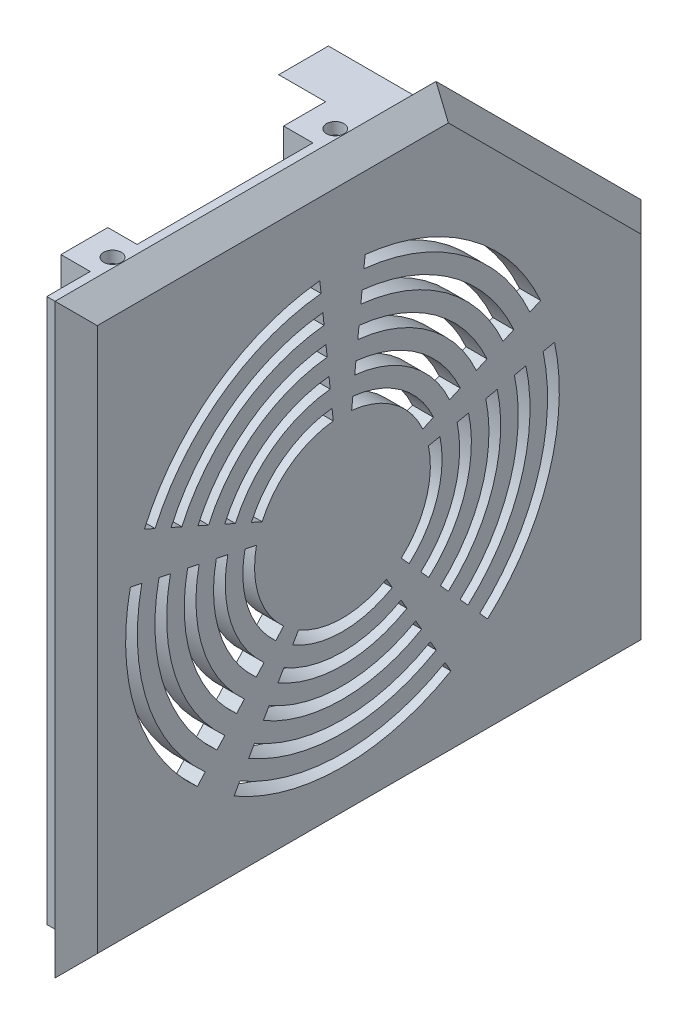
SolidWorks part; units mm, degrees
ref_plane "Front Plane" through (0, 0, 0) normal (0, 0, 1) x (1, 0, 0)
ref_plane "Top Plane" through (0, 0, 0) normal (0, 1, 0) x (1, 0, 0)
ref_plane "Right Plane" through (0, 0, 0) normal (1, 0, 0) x (0, 0, -1)
sketch "Sketch1" plane through (0, 0, 0) normal (1, 0, 0) x (0, 0, -1)
  line L0 (-8.4475, 4.8927) -> (-8.4475, -95.1073)
  line L1 (-8.4475, -95.1073) -> (91.5525, -95.1073)
  line L2 (91.5525, -95.1073) -> (91.5525, -30.1073)
  line L3 (91.5525, -30.1073) -> (56.5525, 4.8927)
  line L4 (56.5525, 4.8927) -> (-8.4475, 4.8927)
  dimension "D1" = 100
  dimension "D2" = 100
  dimension "D3" = 135
  dimension "D4" = 65
extrude "Boss-Extrude1" add sketch "Sketch1" along normal blind 3.6 draft 45
sketch "Sketch2" plane through (0, 0, 0) normal (-1, 0, 0) x (0, 0, 1)
  line L0 (-56.1927, 1.2927) -> (4.8475, 1.2927) construction
  line L1 (4.8475, 1.2927) -> (4.8475, -91.5073) construction
  line L2 (4.8475, -91.5073) -> (-87.9525, -91.5073) construction
  line L3 (-87.9525, -91.5073) -> (-87.9525, -30.4671) construction
  line L4 (-87.9525, -30.4671) -> (-56.1927, 1.2927) construction
  line L5 (-56.5525, 4.8927) -> (8.4475, 4.8927) construction
  line L6 (8.4475, 4.8927) -> (8.4475, -95.1073) construction
  line L7 (-91.5525, -95.1073) -> (-91.5525, -30.1073) construction
  line L8 (8.4475, -95.1073) -> (-91.5525, -95.1073) construction
  line L9 (-91.5525, -30.1073) -> (-56.5525, 4.8927) construction
  line L10 (-56.1927, 1.2927) -> (4.8475, 1.2927)
  line L11 (4.8475, 1.2927) -> (4.8475, -91.5073)
  line L12 (4.8475, -91.5073) -> (-87.9525, -91.5073)
  line L13 (-87.9525, -91.5073) -> (-87.9525, -30.4671)
  line L14 (-87.9525, -30.4671) -> (-56.1927, 1.2927)
  dimension "D1" = 3.6
  dimension "D2" = 3.6
  dimension "D3" = 3.6
  dimension "D4" = 3.6
  dimension "D5" = 3.6
  dimension "D6" = 2.8
extrude "Extrude-Thin2" add sketch "Sketch2" along normal blind 5 thin
sketch "Sketch5" plane through (0, 0, 0) normal (-1, 0, 0) x (0, 0, 1)
  line L0 (4.8475, -91.5073) -> (-87.9525, -91.5073) construction
  line L1 (-70.5525, -91.5073) -> (-62.5525, -91.5073)
  line L2 (-70.5525, -91.5073) -> (-70.5525, -83.5073)
  line L3 (-70.5525, -83.5073) -> (-62.5525, -83.5073)
  line L4 (-62.5525, -91.5073) -> (-62.5525, -83.5073)
  line L5 (-91.5525, -95.1073) -> (-91.5525, -30.1073) construction
  line L6 (-20.5525, -91.5073) -> (-12.5525, -91.5073)
  line L7 (-20.5525, -91.5073) -> (-20.5525, -83.5073)
  line L8 (-20.5525, -83.5073) -> (-12.5525, -83.5073)
  line L9 (-12.5525, -91.5073) -> (-12.5525, -83.5073)
  line L10 (8.4475, 4.8927) -> (8.4475, -95.1073) construction
  point P10 (-66.5525, -83.5073)
  point P13 (-16.5525, -83.5073)
  dimension "D1" = 8
  dimension "D2" = 25
  dimension "8" = 8
  dimension "D3" = 25
extrude "Boss-Extrude2" add sketch "Sketch5" along normal blind 10
ref_plane "Plane1" through (0, -85.5073, 0) normal (0, 1, 0) x (1, 0, 0)
sketch "Sketch6" plane through (0, -85.5073, 0) normal (0, 1, 0) x (1, 0, 0)
  line L5 (-10, 69.5525) -> (-3.7321, 69.5525)
  line L6 (-10, 70.5525) -> (-10, 62.5525) construction
  line L7 (-3.7321, 69.5525) -> (-2, 66.5525)
  line L8 (-2, 66.5525) -> (-3.7321, 63.5525)
  line L9 (-3.7321, 63.5525) -> (-10, 63.5525)
  line L10 (-10, 63.5525) -> (-10, 69.5525)
  line L16 (-10, 19.5525) -> (-3.7321, 19.5525)
  line L17 (-3.7321, 19.5525) -> (-2, 16.5525)
  line L18 (-2, 16.5525) -> (-3.7321, 13.5525)
  line L19 (-3.7321, 13.5525) -> (-10, 13.5525)
  line L20 (-10, 13.5525) -> (-10, 19.5525)
  line L21 (-10, 20.5525) -> (-10, 12.5525) construction
  point P12 (-10, 66.5525)
  point P13 (-10, 66.5525)
  point P21 (-10, 16.5525)
  point P22 (-10, 16.5525)
  dimension "D1" = 6
  dimension "D2" = 8
  dimension "D6" = 120
  dimension "D7" = 6
  dimension "D8" = 120
  dimension "D9" = 8
extrude "Cut-Extrude1" cut sketch "Sketch6" against normal blind 4
hole_wizard "Ø3.0mm Dowel Hole1" positions "Sketch9" profile "Sketch10" hole size "Ø3.0" standard "BSI"
sketch "Sketch9" plane through (0, -91.5073, 0) normal (0, -1, 0) x (-1, 0, 0)
  point P0 (5.2, 66.5525)
  point P2 (5.2, 16.5525)
  dimension "D1" = 3.2
sketch "Sketch10" plane through (-5.2, -91.5073, -66.5525) normal (1, 0, 0) x (0, 0, -1)
  line L0 (0, 0) -> (0, 8.9013)
  line L1 (0, 8.9013) -> (1.5, 8)
  line L2 (1.5, 8) -> (1.5, 0)
  line L5 (1.5, 0) -> (0, 0)
  line L10 (0, 8.9013) -> (-1.5, 8) construction
  line L11 (0, -6.35) -> (0, 107.95) construction
  dimension "Hole Dia." = 3
  dimension "Hole Depth" = 8
  dimension "Drill Angle" = 118
sketch "Sketch11" plane through (0, 0, 0) normal (-1, 0, 0) x (0, 0, 1)
  line L0 (-56.1927, 1.2927) -> (4.8475, 1.2927) construction
  line L1 (-2.5525, 1.2927) -> (-10.5525, 1.2927)
  line L2 (-2.5525, 1.2927) -> (-2.5525, -6.7073)
  line L3 (-2.5525, -6.7073) -> (-10.5525, -6.7073)
  line L4 (-10.5525, 1.2927) -> (-10.5525, -6.7073)
  line L5 (-62.5525, -83.5073) -> (-70.5525, -83.5073) construction
  line L6 (-48.5525, 1.2927) -> (-40.5525, 1.2927)
  line L7 (-48.5525, 1.2927) -> (-48.5525, -6.7073)
  line L8 (-48.5525, -6.7073) -> (-40.5525, -6.7073)
  line L9 (-40.5525, 1.2927) -> (-40.5525, -6.7073)
  line L10 (-62.5525, -91.5073) -> (-62.5525, -83.5073) construction
  line L13 (8.4475, 4.8927) -> (8.4475, -95.1073) construction
  point P16 (-44.5525, 1.2927)
  point P19 (-6.5525, 1.2927)
  dimension "D1" = 15
  dimension "D2" = 12
extrude "Boss-Extrude3" add sketch "Sketch11" along normal up to surface (10 mm away)
ref_plane "Plane2" through (0, -0.7073, 0) normal (0, 1, 0) x (1, 0, 0)
sketch "Sketch13" plane through (0, -0.7073, 0) normal (0, 1, 0) x (1, 0, 0)
  line L0 (-10, 9.5525) -> (-3.7321, 9.5525)
  line L1 (-3.7321, 9.5525) -> (-2, 6.5525)
  line L2 (-2, 6.5525) -> (-3.7321, 3.5525)
  line L3 (-3.7321, 3.5525) -> (-10, 3.5525)
  line L4 (-10, 3.5525) -> (-10, 9.5525)
  line L5 (-10, 10.5525) -> (-10, 2.5525) construction
  line L6 (-10, 47.5525) -> (-3.7321, 47.5525)
  line L7 (-3.7321, 47.5525) -> (-2, 44.5525)
  line L8 (-2, 44.5525) -> (-3.7321, 41.5525)
  line L9 (-3.7321, 41.5525) -> (-10, 41.5525)
  line L10 (-10, 41.5525) -> (-10, 47.5525)
  line L11 (-10, 48.5525) -> (-10, 40.5525) construction
  point P7 (-10, 6.5525)
  point P8 (-10, 6.5525)
  point P14 (-10, 44.5525)
  point P17 (-10, 44.5525)
  dimension "D1" = 6
  dimension "D2" = 120
  dimension "D3" = 8
  dimension "D4" = 6
  dimension "D5" = 120
  dimension "D6" = 8
extrude "Cut-Extrude2" cut sketch "Sketch13" against normal blind 4
hole_wizard "Ø3.0mm Dowel Hole2" positions "Sketch14" profile "Sketch15" hole size "Ø3.0" standard "BSI"
sketch "Sketch14" plane through (0, 1.2927, 0) normal (0, 1, 0) x (1, 0, 0)
  point P0 (-122.1853, 54.0527)
  point P2 (-5.2, 44.5525)
  point P4 (-5.2, 6.5525)
  dimension "D1" = 3.2
  dimension "D2" = 3.2
sketch "Sketch15" plane through (-122.1853, 1.2927, -54.0527) normal (1, 0, 0) x (0, 0, 1)
  line L0 (0, 0) -> (0, 8.9013)
  line L1 (0, 8.9013) -> (1.5, 8)
  line L2 (1.5, 8) -> (1.5, 0)
  line L5 (1.5, 0) -> (0, 0)
  line L10 (0, 8.9013) -> (-1.5, 8) construction
  line L11 (0, -6.35) -> (0, 107.95) construction
  dimension "Hole Dia." = 3
  dimension "Hole Depth" = 8
  dimension "Drill Angle" = 118
sketch "Sketch16" plane through (0, 0, 0) normal (-1, 0, 0) x (0, 0, 1)
  line L0 (-56.1927, 1.2927) -> (4.8475, 1.2927) construction
  line L1 (-47.7074, 1.2927) -> (-87.9525, -38.9524)
  line L2 (-87.9525, -91.5073) -> (-87.9525, -30.4671) construction
  line L3 (-87.9525, -38.9524) -> (-87.9525, -30.4671)
  line L4 (-87.9525, -30.4671) -> (-56.1927, 1.2927)
  line L5 (-56.1927, 1.2927) -> (-47.7074, 1.2927)
  dimension "D1" = 6
extrude "Boss-Extrude4" add sketch "Sketch16" along normal blind 18
sketch "Sketch17" plane through (-18, 0, 0) normal (-1, 0, 0) x (0, 0, 1)
  line L0 (-57.2234, -2.8492) -> (-55.8092, -4.2634)
  line L1 (-55.8092, -4.2634) -> (-82.3964, -30.8507)
  line L2 (-82.3964, -30.8507) -> (-83.8106, -29.4364)
  line L3 (-83.8106, -29.4364) -> (-57.2234, -2.8492)
  line L4 (-91.5525, -30.1073) -> (-56.5525, 4.8927) construction
  line L5 (-87.9525, -30.4671) -> (-56.1927, 1.2927) construction
  line L6 (-74.0525, -12.6073) -> (-70.517, -16.1428) construction
  dimension "D1" = 2
  dimension "D2" = 2.2
  dimension "D3" = 37.6
extrude "Cut-Extrude3" cut sketch "Sketch17" against normal blind 6
sketch "Sketch18" plane through (0, 0, 0) normal (-1, 0, 0) x (0, 0, 1)
  line L24 (-36.9898, -47.8542) -> (-12.6985, -89.928) construction
  line L25 (-36.9898, -47.8542) -> (-61.2476, -89.8699) construction
  line L26 (-29.4898, -60.8446) -> (-28.4898, -62.5766)
  line L27 (-26.9898, -65.1747) -> (-25.9898, -66.9068)
  line L28 (-24.4898, -69.5048) -> (-23.4898, -71.2369)
  line L29 (-21.9898, -73.835) -> (-20.9898, -75.567)
  line L30 (-44.4898, -60.8446) -> (-45.4898, -62.5766)
  line L31 (-46.9898, -65.1747) -> (-47.9898, -66.9068)
  line L32 (-49.4898, -69.5048) -> (-50.4898, -71.2369)
  line L33 (-51.9898, -73.835) -> (-52.9898, -75.567)
  line L34 (-19.4898, -78.1651) -> (-18.4898, -79.8971)
  line L35 (-54.4898, -78.1651) -> (-55.4898, -79.8971)
  line L36 (-47.0268, -59.0014) -> (-48.365, -60.4877)
  line L37 (-50.3724, -62.7171) -> (-51.7107, -64.2034)
  line L38 (-53.7181, -66.4328) -> (-55.0564, -67.9191)
  line L39 (-57.0637, -70.1485) -> (-58.402, -71.6348)
  line L40 (-51.662, -44.7355) -> (-53.6183, -44.3197)
  line L41 (-56.5528, -43.696) -> (-58.5091, -43.2801)
  line L42 (-61.4435, -42.6564) -> (-63.3998, -42.2406)
  line L43 (-66.3343, -41.6168) -> (-68.2905, -41.201)
  line L44 (-60.4094, -73.8643) -> (-61.7477, -75.3506)
  line L45 (-71.225, -40.5773) -> (-73.1813, -40.1615)
  line L46 (-50.693, -41.7531) -> (-52.5201, -40.9397)
  line L47 (-55.2607, -39.7195) -> (-57.0878, -38.906)
  line L48 (-59.8285, -37.6858) -> (-61.6556, -36.8723)
  line L49 (-64.3962, -35.6521) -> (-66.2233, -34.8386)
  line L50 (-38.5578, -32.9364) -> (-38.7668, -30.9473)
  line L51 (-39.0804, -27.9638) -> (-39.2895, -25.9747)
  line L52 (-39.603, -22.9911) -> (-39.8121, -21.0021)
  line L53 (-40.1257, -18.0185) -> (-40.3347, -16.0295)
  line L54 (-68.9639, -33.6184) -> (-70.791, -32.8049)
  line L55 (-40.6483, -13.0459) -> (-40.8574, -11.0569)
  line L56 (-35.4219, -32.9364) -> (-35.2128, -30.9473)
  line L57 (-34.8993, -27.9638) -> (-34.6902, -25.9747)
  line L58 (-34.3766, -22.9911) -> (-34.1676, -21.0021)
  line L59 (-33.854, -18.0185) -> (-33.6449, -16.0295)
  line L60 (-23.2866, -41.7531) -> (-21.4596, -40.9397)
  line L61 (-18.7189, -39.7195) -> (-16.8918, -38.906)
  line L62 (-14.1512, -37.6858) -> (-12.3241, -36.8723)
  line L63 (-9.5835, -35.6521) -> (-7.7564, -34.8386)
  line L64 (-33.3313, -13.0459) -> (-33.1223, -11.0569)
  line L65 (-5.0157, -33.6184) -> (-3.1886, -32.8049)
  line L66 (-22.3176, -44.7355) -> (-20.3613, -44.3197)
  line L67 (-17.4269, -43.696) -> (-15.4706, -43.2801)
  line L68 (-12.5361, -42.6564) -> (-10.5798, -42.2406)
  line L69 (-7.6454, -41.6168) -> (-5.6891, -41.201)
  line L70 (-26.9529, -59.0014) -> (-25.6146, -60.4877)
  line L71 (-23.6072, -62.7171) -> (-22.269, -64.2034)
  line L72 (-20.2616, -66.4328) -> (-18.9233, -67.9191)
  line L73 (-16.9159, -70.1485) -> (-15.5776, -71.6348)
  line L74 (-2.7547, -40.5773) -> (-0.7984, -40.1615)
  line L75 (-13.5703, -73.8643) -> (-12.232, -75.3506)
  arc A0 (-29.4898, -60.8446) -> (-44.4898, -60.8446) centre (-36.9898, -47.8542) cw
  arc A1 (-28.4898, -62.5766) -> (-45.4898, -62.5766) centre (-36.9898, -47.8542) cw
  arc A2 (-26.9898, -65.1747) -> (-46.9898, -65.1747) centre (-36.9898, -47.8542) cw
  arc A3 (-25.9898, -66.9068) -> (-47.9898, -66.9068) centre (-36.9898, -47.8542) cw
  arc A4 (-24.4898, -69.5048) -> (-49.4898, -69.5048) centre (-36.9898, -47.8542) cw
  arc A5 (-23.4898, -71.2369) -> (-50.4898, -71.2369) centre (-36.9898, -47.8542) cw
  arc A6 (-21.9898, -73.835) -> (-51.9898, -73.835) centre (-36.9898, -47.8542) cw
  arc A7 (-20.9898, -75.567) -> (-52.9898, -75.567) centre (-36.9898, -47.8542) cw
  arc A8 (-19.4898, -78.1651) -> (-54.4898, -78.1651) centre (-36.9898, -47.8542) cw
  arc A9 (-18.4898, -79.8971) -> (-55.4898, -79.8971) centre (-36.9898, -47.8542) cw
  arc A10 (-47.0268, -59.0014) -> (-51.662, -44.7355) centre (-36.9898, -47.8542) cw
  arc A11 (-48.365, -60.4877) -> (-53.6183, -44.3197) centre (-36.9898, -47.8542) cw
  arc A12 (-50.3724, -62.7171) -> (-56.5528, -43.696) centre (-36.9898, -47.8542) cw
  arc A13 (-51.7107, -64.2034) -> (-58.5091, -43.2801) centre (-36.9898, -47.8542) cw
  arc A14 (-53.7181, -66.4328) -> (-61.4435, -42.6564) centre (-36.9898, -47.8542) cw
  arc A15 (-55.0564, -67.9191) -> (-63.3998, -42.2406) centre (-36.9898, -47.8542) cw
  arc A16 (-57.0637, -70.1485) -> (-66.3343, -41.6168) centre (-36.9898, -47.8542) cw
  arc A17 (-58.402, -71.6348) -> (-68.2905, -41.201) centre (-36.9898, -47.8542) cw
  arc A18 (-60.4094, -73.8643) -> (-71.225, -40.5773) centre (-36.9898, -47.8542) cw
  arc A19 (-61.7477, -75.3506) -> (-73.1813, -40.1615) centre (-36.9898, -47.8542) cw
  arc A20 (-50.693, -41.7531) -> (-38.5578, -32.9364) centre (-36.9898, -47.8542) cw
  arc A21 (-52.5201, -40.9397) -> (-38.7668, -30.9473) centre (-36.9898, -47.8542) cw
  arc A22 (-55.2607, -39.7195) -> (-39.0804, -27.9638) centre (-36.9898, -47.8542) cw
  arc A23 (-57.0878, -38.906) -> (-39.2895, -25.9747) centre (-36.9898, -47.8542) cw
  arc A24 (-59.8285, -37.6858) -> (-39.603, -22.9911) centre (-36.9898, -47.8542) cw
  arc A25 (-61.6556, -36.8723) -> (-39.8121, -21.0021) centre (-36.9898, -47.8542) cw
  arc A26 (-64.3962, -35.6521) -> (-40.1257, -18.0185) centre (-36.9898, -47.8542) cw
  arc A27 (-66.2233, -34.8386) -> (-40.3347, -16.0295) centre (-36.9898, -47.8542) cw
  arc A28 (-68.9639, -33.6184) -> (-40.6483, -13.0459) centre (-36.9898, -47.8542) cw
  arc A29 (-70.791, -32.8049) -> (-40.8574, -11.0569) centre (-36.9898, -47.8542) cw
  arc A30 (-35.4219, -32.9364) -> (-23.2866, -41.7531) centre (-36.9898, -47.8542) cw
  arc A31 (-35.2128, -30.9473) -> (-21.4596, -40.9397) centre (-36.9898, -47.8542) cw
  arc A32 (-34.8993, -27.9638) -> (-18.7189, -39.7195) centre (-36.9898, -47.8542) cw
  arc A33 (-34.6902, -25.9747) -> (-16.8918, -38.906) centre (-36.9898, -47.8542) cw
  arc A34 (-34.3766, -22.9911) -> (-14.1512, -37.6858) centre (-36.9898, -47.8542) cw
  arc A35 (-34.1676, -21.0021) -> (-12.3241, -36.8723) centre (-36.9898, -47.8542) cw
  arc A36 (-33.854, -18.0185) -> (-9.5835, -35.6521) centre (-36.9898, -47.8542) cw
  arc A37 (-33.6449, -16.0295) -> (-7.7564, -34.8386) centre (-36.9898, -47.8542) cw
  arc A38 (-33.3313, -13.0459) -> (-5.0157, -33.6184) centre (-36.9898, -47.8542) cw
  arc A39 (-33.1223, -11.0569) -> (-3.1886, -32.8049) centre (-36.9898, -47.8542) cw
  arc A40 (-22.3176, -44.7355) -> (-26.9529, -59.0014) centre (-36.9898, -47.8542) cw
  arc A41 (-20.3613, -44.3197) -> (-25.6146, -60.4877) centre (-36.9898, -47.8542) cw
  arc A42 (-17.4269, -43.696) -> (-23.6072, -62.7171) centre (-36.9898, -47.8542) cw
  arc A43 (-15.4706, -43.2801) -> (-22.269, -64.2034) centre (-36.9898, -47.8542) cw
  arc A44 (-12.5361, -42.6564) -> (-20.2616, -66.4328) centre (-36.9898, -47.8542) cw
  arc A45 (-10.5798, -42.2406) -> (-18.9233, -67.9191) centre (-36.9898, -47.8542) cw
  arc A46 (-7.6454, -41.6168) -> (-16.9159, -70.1485) centre (-36.9898, -47.8542) cw
  arc A47 (-5.6891, -41.201) -> (-15.5776, -71.6348) centre (-36.9898, -47.8542) cw
  arc A48 (-2.7547, -40.5773) -> (-13.5703, -73.8643) centre (-36.9898, -47.8542) cw
  arc A49 (-0.7984, -40.1615) -> (-12.232, -75.3506) centre (-36.9898, -47.8542) cw
  point P21 (-36.9898, -62.8542)
  point P22 (-36.9898, -64.8542)
  point P23 (-36.9898, -67.8542)
  point P24 (-36.9898, -69.8542)
  point P25 (-36.9898, -72.8542)
  point P26 (-36.9898, -74.8542)
  point P27 (-36.9898, -77.8542)
  point P28 (-36.9898, -79.8542)
  dimension "D1" = 60
extrude "Cut-Extrude4" cut sketch "Sketch18" against normal up to next (3.6 mm away)
